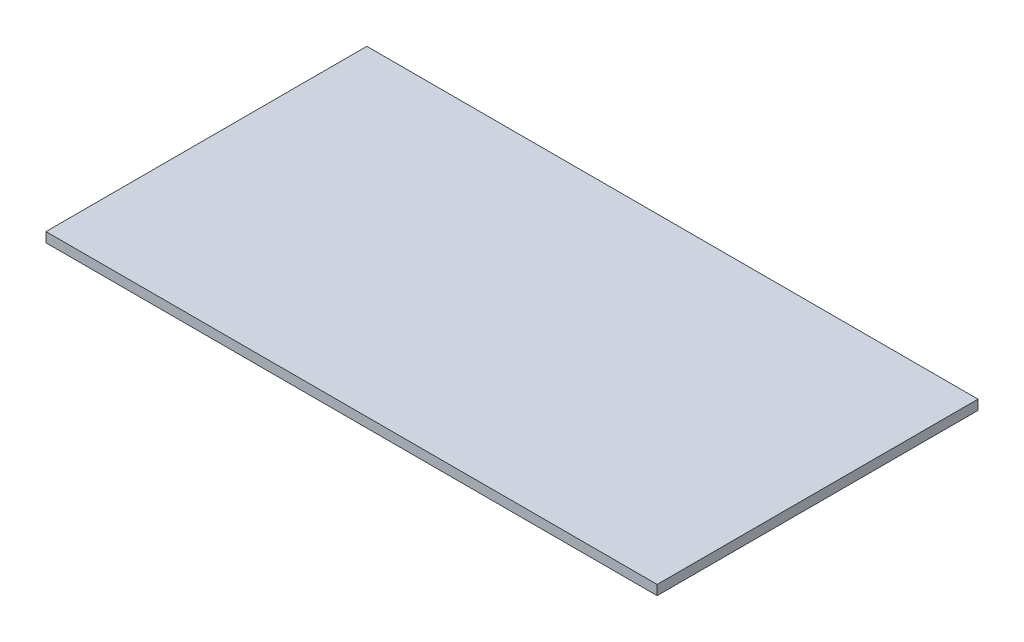
SolidWorks part; units mm, degrees
ref_plane "Front Plane" through (0, 0, 0) normal (0, 0, 1) x (1, 0, 0)
ref_plane "Top Plane" through (0, 0, 0) normal (0, 1, 0) x (1, 0, 0)
ref_plane "Right Plane" through (0, 0, 0) normal (1, 0, 0) x (0, 0, -1)
sketch "Sketch1" plane through (0, 0, 0) normal (0, 1, 0) x (1, 0, 0)
  line L0 (0, 0) -> (101.6, 0)
  line L1 (101.6, 0) -> (101.6, 53.34)
  line L2 (101.6, 53.34) -> (0, 53.34)
  line L3 (0, 53.34) -> (0, 0)
extrude "Boss-Extrude1" add sketch "Sketch1" along normal blind 1.6256
